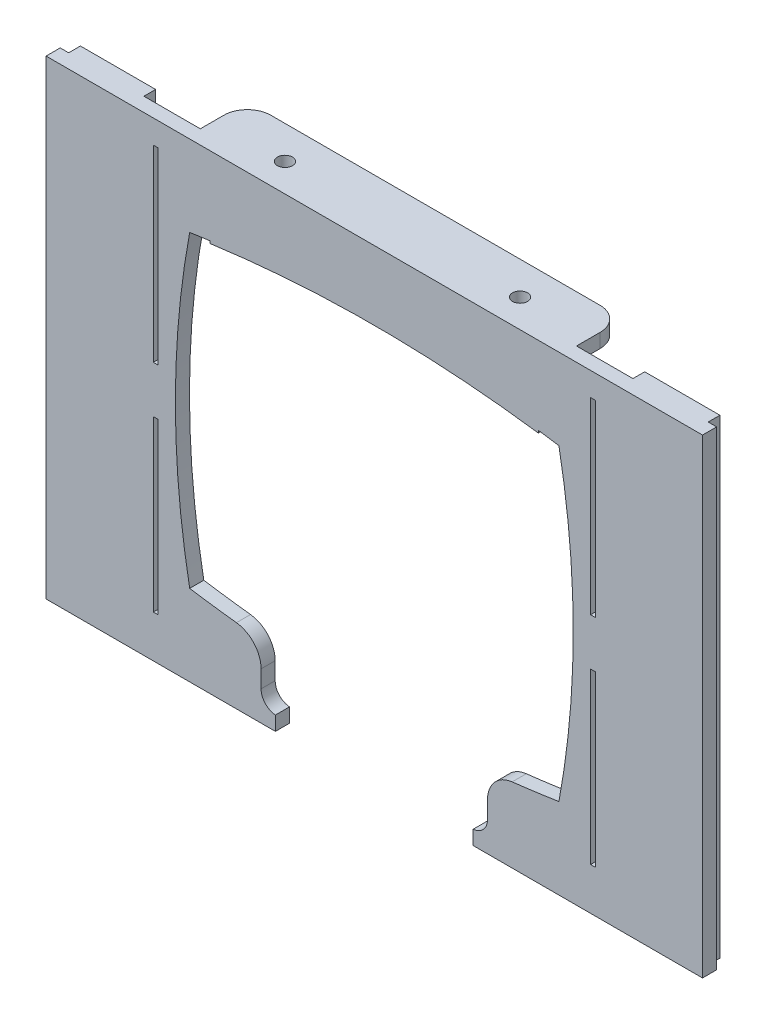
SolidWorks part; units mm, degrees
ref_plane "Front Plane" through (0, 0, 0) normal (0, 0, 1) x (1, 0, 0)
ref_plane "Top Plane" through (0, 0, 0) normal (0, 1, 0) x (1, 0, 0)
ref_plane "Right Plane" through (0, 0, 0) normal (1, 0, 0) x (0, 0, -1)
sketch "Sketch1" plane through (0, 0, 0) normal (0, 0, 1) x (1, 0, 0)
  line L1 (70, -50) -> (-70, -50)
  line L2 (70, -50) -> (70, 50)
  line L3 (70, 50) -> (-70, 50)
  line L4 (-70, -50) -> (-70, 50)
  line L5 (70, -50) -> (-70, 50) construction
  line L6 (70, 50) -> (-70, -50) construction
  point P0 (0, 0)
  dimension "D1" = 140
  dimension "D2" = 100
extrude "Boss-Extrude1" add sketch "Sketch1" along normal blind 3
sketch "Sketch2" plane through (0, 0, 0) normal (0, 0, -1) x (-1, 0, 0)
  line L0 (-60, 63.7201) -> (-60, -49936.2799) construction
  line L1 (60, 64.2305) -> (60, -49935.7695) construction
  dimension "D1" = 60
  dimension "D2" = 60
sketch "Sketch3" plane through (0, 0, 0) normal (0, 0, -1) x (-1, 0, 0)
  line L0 (-60, 200063.7201) -> (-60, -249936.2799) construction
  line L1 (-52, -50) -> (-68, -50)
  line L2 (-52, -50) -> (-52, 50)
  line L3 (-52, 50) -> (-68, 50)
  line L4 (-68, -50) -> (-68, 50)
  line L5 (-52, -50) -> (-68, 50) construction
  line L6 (-52, 50) -> (-68, -50) construction
  line L7 (-70, 50) -> (70, 50) construction
  line L8 (60, 200064.2305) -> (60, -249935.7695) construction
  line L9 (68, -50) -> (52, -50)
  line L10 (68, -50) -> (68, 50)
  line L11 (68, 50) -> (52, 50)
  line L12 (52, -50) -> (52, 50)
  line L13 (68, -50) -> (52, 50) construction
  line L14 (68, 50) -> (52, -50) construction
  point P0 (-60, 0)
  point P9 (60, 0)
  dimension "D1" = 16
  dimension "D2" = 16
extrude "Boss-Extrude2" add sketch "Sketch3" along normal blind 2.5
sketch "Sketch4" plane through (0, 0, -2.5) normal (0, 0, -1) x (-1, 0, 0)
  line L0 (-60, 200063.7201) -> (-60, -249936.2799) construction
  line L1 (-66.25, 47.75) -> (-53.75, 47.75)
  line L2 (-66.25, 47.75) -> (-66.25, 42.25)
  line L3 (-66.25, 42.25) -> (-53.75, 42.25)
  line L4 (-53.75, 47.75) -> (-53.75, 42.25)
  line L5 (-66.25, 47.75) -> (-53.75, 42.25) construction
  line L6 (-66.25, 42.25) -> (-53.75, 47.75) construction
  line L7 (-52, 50) -> (-68, 50) construction
  point P0 (-60, 45)
  dimension "D1" = 12.5
  dimension "D2" = 5
  dimension "D3" = 5.5
extrude "Cut-Extrude1" cut sketch "Sketch4" against normal blind 1.5
mirror "Mirror1" about plane through (0, 0, 0) normal (1, 0, 0) of "Cut-Extrude1"
pattern_linear "LPattern1" count 4 spacing 30 along (0, -1, 0) of "Mirror1", "Cut-Extrude1"
sketch "Sketch6" plane through (0, 50, 0) normal (0, 1, 0) x (1, 0, 0)
  line L0 (70, -3) -> (-70, -3) construction
  line L1 (-70, 0) -> (-69.8, 0)
  line L2 (-70, 0) -> (-70, -3)
  line L3 (-70, -3) -> (-69.8, -3)
  line L4 (-69.8, 0) -> (-69.8, -3)
  line L6 (70, 0) -> (69.8, 0)
  line L7 (70, 0) -> (70, -3)
  line L8 (70, -3) -> (69.8, -3)
  line L9 (69.8, 0) -> (69.8, -3)
  dimension "D1" = 0.2
  dimension "D2" = 0.2
extrude "Cut-Extrude3" cut sketch "Sketch6" against normal through all both and the other way through all
sketch "Sketch8" plane through (0, 0, 3) normal (0, 0, 1) x (1, 0, 0)
  line L0 (-60, 10.6106) -> (-60, -49989.3894) construction
  line L1 (60, 23.1735) -> (60, -49976.8265) construction
  dimension "D1" = 60
  dimension "D2" = 60
sketch "Sketch10" plane through (0, 0, 3) normal (0, 0, 1) x (1, 0, 0)
  line L0 (-66, -50) -> (-54, -50) construction
  line L1 (-60, 200010.6106) -> (-60, -249989.3894) construction
  line L2 (-69.8, -50) -> (69.8, -50) construction
  line L3 (-66, -44) -> (-54, -44)
  line L4 (-66, -56) -> (-54, -56)
  arc A0 (-66, -44) -> (-66, -56) centre (-66, -50) ccw
  arc A1 (-54, -56) -> (-54, -44) centre (-54, -50) ccw
  point P6 (-60, -50)
  dimension "D1" = 12
  dimension "D2" = 12
extrude "Cut-Extrude4" [suppressed] cut sketch "Sketch10" against normal through all both and the other way through all
mirror "Mirror3" [suppressed] about plane through (0, 0, 0) normal (1, 0, 0)
sketch "Sketch11" plane through (0, 0, -2.5) normal (0, 0, -1) x (-1, 0, 0)
  line L0 (-53.75, 12.25) -> (-60, -7.75)
  line L1 (-60, 200063.7201) -> (-60, -249936.2799) construction
  line L2 (-60, -7.75) -> (-66.25, 12.25)
  line L3 (-66.25, 12.25) -> (-53.75, 12.25)
  dimension "D1" = 20
extrude "Cut-Extrude5" cut sketch "Sketch11" against normal blind 1.5
pattern_linear "LPattern2" count 2 spacing 30 along (0, 1, 0) count 2 spacing 30 along (0, -1, 0) of "Cut-Extrude5"
mirror "Mirror4" about plane through (0, 0, 0) normal (1, 0, 0) of "LPattern2", "Cut-Extrude5"
sketch "Sketch13" plane through (0, 0, 0) normal (0, 0, -1) x (-1, 0, 0)
  line L0 (-52, -50) -> (-52, 50) construction
  line L1 (-47, 45) -> (-46, 45)
  line L2 (-47, 45) -> (-47, 5)
  line L3 (-47, 5) -> (-46, 5)
  line L4 (-46, 45) -> (-46, 5)
  line L5 (-52, -50) -> (-52, 50) construction
  line L8 (-47, -5) -> (-46, -5)
  line L9 (-47, -5) -> (-47, -41)
  line L10 (-47, -41) -> (-46, -41)
  line L11 (-46, -5) -> (-46, -41)
  dimension "D1" = 5
  dimension "D2" = 1
  dimension "D3" = 40
  dimension "D4" = 5
  dimension "D5" = 5
  dimension "D6" = 36
  dimension "D7" = 5
  dimension "D8" = 1
extrude "Cut-Extrude7" cut sketch "Sketch13" against normal blind 10
mirror "Mirror7" about plane through (0, 0, 0) normal (1, 0, 0) of "Cut-Extrude7"
sketch "Sketch15" plane through (0, 0, 0) normal (0, 0, -1) x (-1, 0, 0)
  line L0 (-52, 50) -> (52, 50) construction
  line L1 (-40, 50) -> (40, 50)
  line L2 (-40, 50) -> (-40, 47)
  line L3 (-40, 47) -> (40, 47)
  line L4 (40, 50) -> (40, 47)
  dimension "D1" = 80
  dimension "D2" = 40
  dimension "D3" = 3
extrude "Boss-Extrude4" add sketch "Sketch15" along normal blind 10
fillet "Fillet2" radius 5 2 edges at (-40, 48.5, -10) (40, 48.5, -10)
fillet "Fillet3" radius 3 1 edges at (0, 47, 0)
sketch "Sketch17" plane through (0, 0, -2.5) normal (0, 0, -1) x (-1, 0, 0)
  line L0 (-68, -50) -> (-52, -50) construction
  line L1 (-66.25, -47.75) -> (-53.9, -47.75)
  line L2 (-66.25, -47.75) -> (-66.25, -50)
  line L3 (-66.25, -50) -> (-53.9, -50)
  line L4 (-53.9, -47.75) -> (-53.9, -50)
extrude "Cut-Extrude9" cut sketch "Sketch17" against normal up to surface (1.5 mm away) up to face at (60, -45, -1)
mirror "Mirror8" about plane through (0, 0, 0) normal (1, 0, 0) of "Cut-Extrude9"
sketch "Sketch18" plane through (0, 50, 0) normal (0, 1, 0) x (1, 0, 0)
  line L0 (25, 3) -> (-25, 3) construction
  line L1 (69.8, -3) -> (-69.8, -3) construction
  circle A0 centre (-25, 3) radius 1.6
  circle A1 centre (25, 3) radius 1.6
  point P3 (0, 3)
  dimension "D3" = 3.2
  dimension "D1" = 6
  dimension "D2" = 50
extrude "Cut-Extrude10" cut sketch "Sketch18" against normal blind 10
sketch "Sketch19" plane through (0, 0, 3) normal (0, 0, 1) x (1, 0, 0)
  line L1 (30, -40) -> (-30, -40) construction
  line L2 (30, -40) -> (30, 40) construction
  line L3 (30, 40) -> (-30, 40) construction
  line L4 (-30, -40) -> (-30, 40) construction
  line L5 (30, -40) -> (-30, 40) construction
  line L6 (30, 40) -> (-30, -40) construction
  point P0 (0, 0)
  dimension "D1" = 60
  dimension "D2" = 80
sketch "Sketch24" plane through (0, 0, 3) normal (0, 0, 1) x (1, 0, 0)
  line L15 (-39.0964, 32.7953) -> (39.0964, -32.7961) construction
  line L16 (39.0964, 32.7953) -> (-39.0964, -32.7961) construction
  line L17 (-24.0786, -40.0004) -> (-24.0786, -43.682)
  line L18 (30, -40.0004) -> (-30, -40.0004) construction
  line L19 (30, -40.0004) -> (30, -36.0004) construction
  line L20 (30, 39.9996) -> (-30, 39.9996) construction
  line L21 (-30, -40.0004) -> (-30, -36.0004) construction
  line L22 (30, -40.0004) -> (27.6, -36.8004) construction
  line L23 (30, 39.9996) -> (-30, -40.0004) construction
  line L24 (-12.5072, -47.5146) -> (12.5072, -47.5146)
  line L25 (24.0786, -43.682) -> (24.0786, -40.0004)
  line L26 (34.9579, 33.4019) -> (34.8865, 32.907)
  line L27 (-34.8865, 32.907) -> (-34.9579, 33.4019)
  line L31 (30, -34.0387) -> (30, 39.9996) construction
  line L32 (27.0472, -36.0633) -> (-30, 39.9996) construction
  line L36 (-30, -34.0387) -> (-30, 39.9996) construction
  circle A39 centre (-30, 39.9996) radius 2.6 construction
  circle A40 centre (30, 39.9996) radius 2.6 construction
  circle A41 centre (30, -40.0004) radius 2.6 construction
  circle A42 centre (-30, -40.0004) radius 2.6 construction
  circle A44 centre (-30, 39.9996) radius 4 construction
  circle A45 centre (30, 39.9996) radius 4 construction
  circle A46 centre (30, -40.0004) radius 4 construction
  circle A47 centre (-30, -40.0004) radius 4 construction
  arc A48 (-39.2618, 32.7696) -> (-39.2618, -32.7704) centre (135.5417, -0.0004) ccw
  arc A49 (-39.2618, -32.7704) -> (-29.32, -34.1182) centre (0, 219.4996) ccw
  arc A50 (-24.0786, -40.0004) -> (-29.32, -34.1182) centre (-30, -40.0004) ccw
  arc A51 (-24.0786, -43.682) -> (-21.0318, -46.9787) centre (-20.7716, -43.682) ccw
  arc A52 (-21.0318, -46.9787) -> (-12.5072, -47.5146) centre (0, 219.4996) ccw
  arc A53 (12.5072, -47.5146) -> (21.0319, -46.9787) centre (0, 219.4996) ccw
  arc A54 (21.0319, -46.9787) -> (24.0786, -43.682) centre (20.7717, -43.682) ccw
  arc A55 (29.32, -34.1182) -> (24.0786, -40.0004) centre (30, -40.0004) ccw
  arc A56 (29.32, -34.1182) -> (39.2619, -32.7704) centre (0, 219.4996) ccw
  arc A57 (39.2619, -32.7704) -> (39.2619, 32.7696) centre (-135.5416, -0.0004) ccw
  arc A58 (39.2619, 32.7696) -> (34.9579, 33.4019) centre (0, -219.5004) ccw
  arc A59 (34.8865, 32.907) -> (-34.8865, 32.907) centre (0, -219.5004) ccw
  arc A60 (-34.9579, 33.4019) -> (-39.2618, 32.7696) centre (0, -219.5004) ccw
  point P0 (0, -0.0004)
  dimension "D3" = 5.2
  dimension "D4" = 8
  dimension "D1" = 60
  dimension "D2" = 80
extrude "Cut-Extrude11" cut sketch "Sketch24" against normal blind 10
sketch "Sketch25" plane through (0, 0, 0) normal (0, 0, -1) x (-1, 0, 0)
  line L0 (12.5072, -47.5146) -> (-12.5072, -47.5146) construction
  line L1 (-21.0319, -45.0292) -> (21.0318, -45.0292)
  line L2 (-21.0319, -45.0292) -> (-21.0319, -50)
  line L3 (-21.0319, -50) -> (21.0318, -50)
  line L4 (21.0318, -45.0292) -> (21.0318, -50)
  line L5 (-21.0319, -45.0292) -> (21.0318, -50) construction
  line L6 (-21.0319, -50) -> (21.0318, -45.0292) construction
  line L7 (52, -50) -> (-52, -50) construction
  point P0 (0, -47.5146)
extrude "Cut-Extrude12" cut sketch "Sketch25" against normal blind 10
